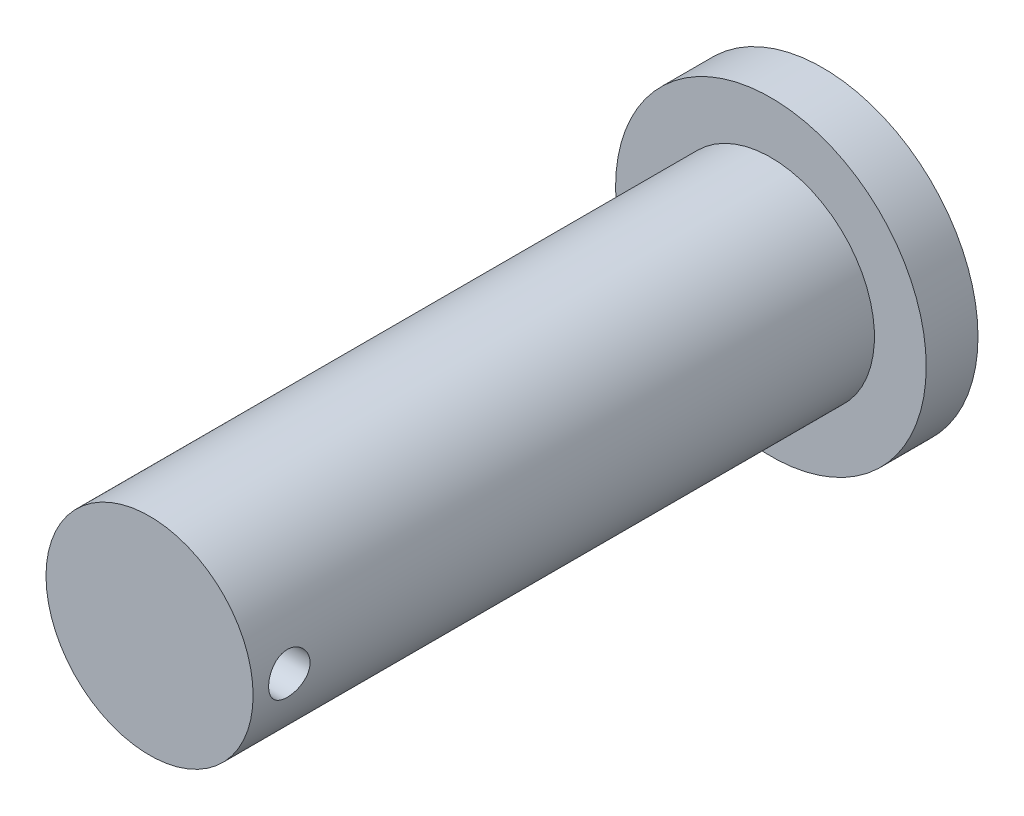
SolidWorks part; units mm, degrees
ref_plane "Front Plane" through (0, 0, 0) normal (0, 0, 1) x (1, 0, 0)
ref_plane "Top Plane" through (0, 0, 0) normal (0, 1, 0) x (1, 0, 0)
ref_plane "Right Plane" through (0, 0, 0) normal (1, 0, 0) x (0, 0, -1)
sketch "Sketch1" plane through (0, 0, 0) normal (0, 0, 1) x (1, 0, 0)
  circle A0 centre (0, 0) radius 10
  dimension "D1" = 20
extrude "Boss-Extrude1" add sketch "Sketch1" along normal blind 65
sketch "Sketch2" plane through (0, 0, 0) normal (1, 0, 0) x (0, 0, -1)
  line L0 (-65, 0) -> (-59, 0) construction
  line L1 (-65, 10) -> (-65, -10) construction
  line L2 (-59, 0) -> (-39, 0) construction
  line L3 (-39, 0) -> (-31, 0) construction
  line L4 (-31, 0) -> (-6, 0) construction
  line L5 (-6, 0) -> (0, 0) construction
  circle A3 centre (-61.5, 0) radius 2
  dimension "D5" = 4
  dimension "D6" = 2.5
  dimension "D1" = 6
  dimension "D2" = 6
  dimension "D3" = 20
  dimension "D4" = 25
extrude "Cut-Extrude1" cut sketch "Sketch2" against normal blind 16 and the other way blind 18
sketch "Sketch5" plane through (0, 0, 0) normal (0, 0, -1) x (-1, 0, 0)
  circle A0 centre (0, 0) radius 15
extrude "Boss-Extrude3" add sketch "Sketch5" against normal blind 5
scale "Scale1" scale about origin uniform scaling yes scale factor 0.5
